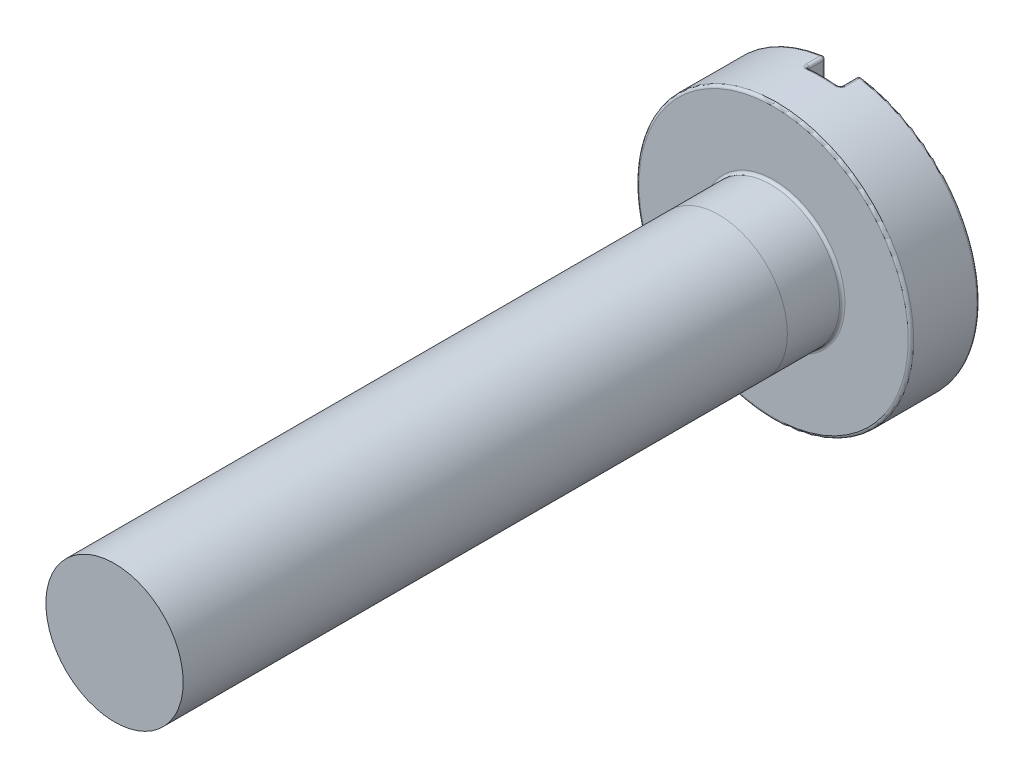
SolidWorks part; units mm, degrees
ref_plane "Front Plane" through (0, 0, 0) normal (0, 0, 1) x (1, 0, 0)
ref_plane "Top Plane" through (0, 0, 0) normal (0, 1, 0) x (1, 0, 0)
ref_plane "Right Plane" through (0, 0, 0) normal (1, 0, 0) x (0, 0, -1)
sketch "Sketch1" plane through (0, 0, 0) normal (0, 0, 1) x (1, 0, 0)
  circle A0 centre (0, 0) radius 1.25
  dimension "D1" = 2.5
extrude "Boss-Extrude1" add sketch "Sketch1" along normal blind 12
sketch "Sketch2" plane through (0, 0, 0) normal (0, 0, 1) x (1, 0, 0)
  circle A2 centre (0, 0) radius 2.5
  circle A3 centre (0, 0) radius 2.5
  dimension "D1" = 1.25
extrude "Boss-Extrude2" add sketch "Sketch2" against normal blind 1.25
sketch "Sketch3" plane through (0, 0, -1.25) normal (0, 0, -1) x (-1, 0, 0)
  line L1 (0.3, -6.7813) -> (-0.3, -6.7813)
  line L2 (0.3, -6.7813) -> (0.3, 6.7813)
  line L3 (0.3, 6.7813) -> (-0.3, 6.7813)
  line L4 (-0.3, -6.7813) -> (-0.3, 6.7813)
  line L5 (0.3, -6.7813) -> (-0.3, 6.7813) construction
  line L6 (0.3, 6.7813) -> (-0.3, -6.7813) construction
  point P0 (0, 0)
  dimension "D1" = 0.6
extrude "Cut-Extrude1" cut sketch "Sketch3" against normal blind 0.35
fillet "Fillet1" radius 0.05 12 edges at (-0.3, -2.4819, -1.075) (-0.3, 2.4819, -1.075) (0.3, 2.4819, -1.075) (0.3, -2.4819, -1.075) (0, 2.5, -0.9) (0, -2.5, -0.9) (0.3, 0, -0.9) (-0.3, 0, -0.9) (-0.3, 0, -1.25) (-2.5, 0, -1.25) (0.3, 0, -1.25) (2.5, 0, -1.25)
fillet "Fillet2" radius 0.05 2 edges at (2.5, 0, 0) (1.25, 0, 0)
sketch "Sketch4" plane through (0, 0, 0) normal (1, 0, 0) x (0, 0, -1)
  line L0 (-1, -3.6683) -> (-1, 4.4314)
  line L1 (-12, 1.25) -> (-12, -1.25) construction
  dimension "D1" = 11
split line "Split Line1"
